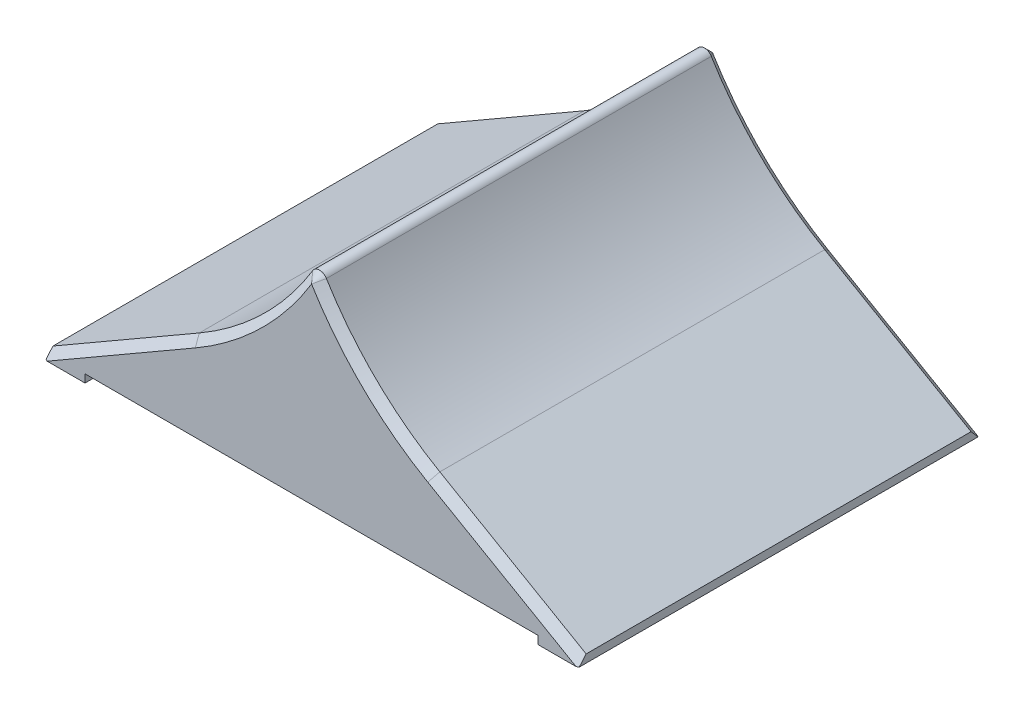
SolidWorks part; units mm, degrees
ref_plane "Front Plane" through (0, 0, 0) normal (0, 0, 1) x (1, 0, 0)
ref_plane "Top Plane" through (0, 0, 0) normal (0, 1, 0) x (1, 0, 0)
ref_plane "Right Plane" through (0, 0, 0) normal (1, 0, 0) x (0, 0, -1)
sketch "Sketch1" plane through (0, 0, 0) normal (0, 1, 0) x (1, 0, 0)
  line L0 (-28.25, 25) -> (-28.25, 15)
  line L1 (-28.25, 15) -> (-31.25, 12)
  line L2 (-31.25, 12) -> (-31.25, -12)
  line L3 (-31.25, -12) -> (-28.25, -15)
  line L4 (-28.25, -15) -> (-28.25, -25)
  line L5 (-28.25, -25) -> (-33.25, -25)
  line L6 (-33.25, -25) -> (-33.25, 25)
  line L7 (-33.25, 25) -> (-28.25, 25)
  line L8 (0, 10.9341) -> (0, -8.4394) construction
  line L9 (33.25, 25) -> (28.25, 25)
  line L10 (33.25, -25) -> (33.25, 25)
  line L11 (28.25, -25) -> (33.25, -25)
  line L12 (28.25, -15) -> (28.25, -25)
  line L13 (31.25, -12) -> (28.25, -15)
  line L14 (31.25, 12) -> (31.25, -12)
  line L15 (28.25, 15) -> (31.25, 12)
  line L16 (28.25, 25) -> (28.25, 15)
  line L17 (-31.25, 0) -> (31.25, 0) construction
  dimension "D1" = 24
  dimension "D2" = 3
  dimension "D3" = 56.5
  dimension "D4" = 2
  dimension "D5" = 50
extrude "Boss-Extrude1" add sketch "Sketch1" along normal blind 1
sketch "Sketch2" plane through (0, 0, 25) normal (0, 0, 1) x (1, 0, 0)
  line L0 (-33.25, 1) -> (33.25, 1)
  line L1 (33.25, 1) -> (15, 11.5366)
  line L2 (-33.25, 1) -> (-15, 11.5366)
  line L3 (0, 0) -> (0, 26.8127) construction
  arc A0 (15, 11.5366) -> (0.8537, 25.3443) centre (35, 46.1777) cw
  arc A1 (-15, 11.5366) -> (-0.8537, 25.3443) centre (-35, 46.1777) ccw
  arc A2 (0.8537, 25.3443) -> (-0.8537, 25.3443) centre (0, 24.8235) ccw
  point P9 (-17.6834, 8.7156)
  point P11 (-22.2005, 7.5872)
  point P16 (-20.696, 8.8936)
  point P17 (0, 0)
  point P18 (-17.5864, 9.8547)
  point P19 (0.8393, 24.4456)
  point P20 (0, 24.9893)
  point P21 (-0.8393, 24.4456)
  point P22 (0, 26.4697)
  point P23 (0, 26.6226)
  point P24 (-46.5212, 48.0303)
  dimension "D1" = 1
  dimension "D4" = 40
  dimension "D2" = 30
  dimension "D3" = 30
extrude "Boss-Extrude2" add sketch "Sketch2" against normal up to surface (50 mm away) up to face at (-30.75, 0.5, -25)
chamfer "Chamfer1" distance 1 angle 45 10 edges at (24.125, 6.2683, -25) (24.125, 6.2683, 25) (7.0604, 17.5528, -25) (7.0604, 17.5528, 25) (0, 25.8235, -25) (0, 25.8235, 25) (-24.125, 6.2683, -25) (-24.125, 6.2683, 25) (-7.0604, 17.5528, -25) (-7.0604, 17.5528, 25)
